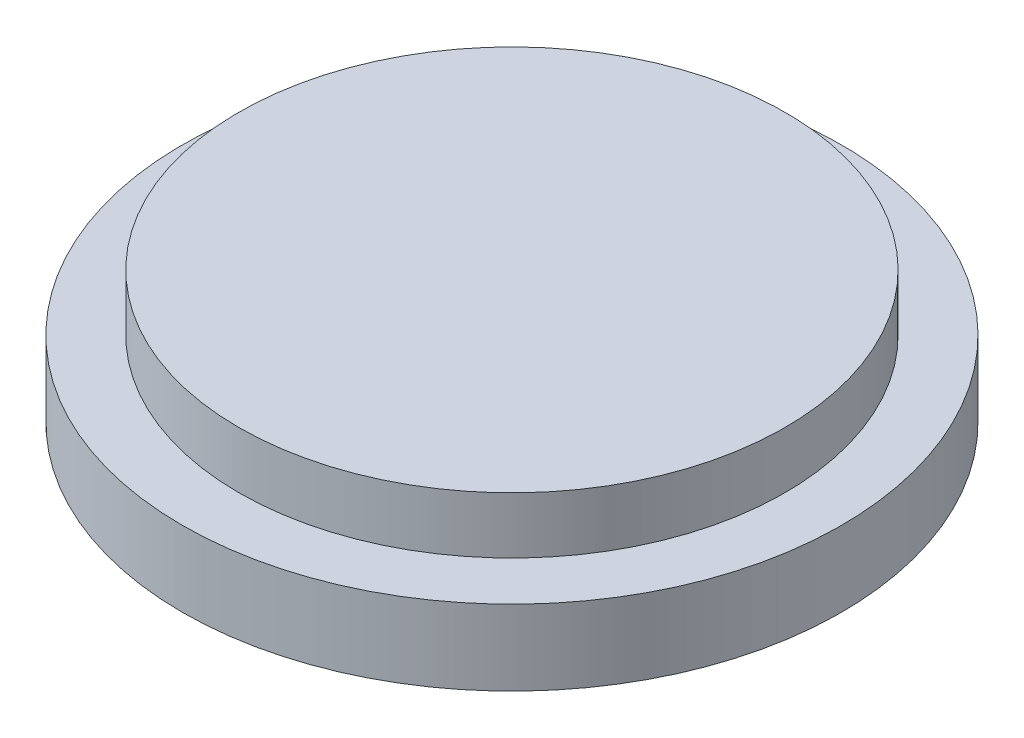
SolidWorks part; units mm, degrees
material "PP Copolymer"
ref_plane "Front Plane" through (0, 0, 0) normal (0, 0, 1) x (1, 0, 0)
ref_plane "Top Plane" through (0, 0, 0) normal (0, 1, 0) x (1, 0, 0)
ref_plane "Right Plane" through (0, 0, 0) normal (1, 0, 0) x (0, 0, -1)
sketch "Cap Head Sketch" plane through (0, 0, 0) normal (0, 1, 0) x (1, 0, 0)
  circle A0 centre (0, 0) radius 35
  dimension "D1" = 70
extrude "Cap Head" add sketch "Cap Head Sketch" along normal blind 8
sketch "Cap Plug Sketch" plane through (0, 0, 0) normal (0, 1, 0) x (1, 0, 0)
  circle A0 centre (0, 0) radius 29
  dimension "D1" = 58
extrude "Cap Plug" add sketch "Cap Plug Sketch" along normal blind 14
